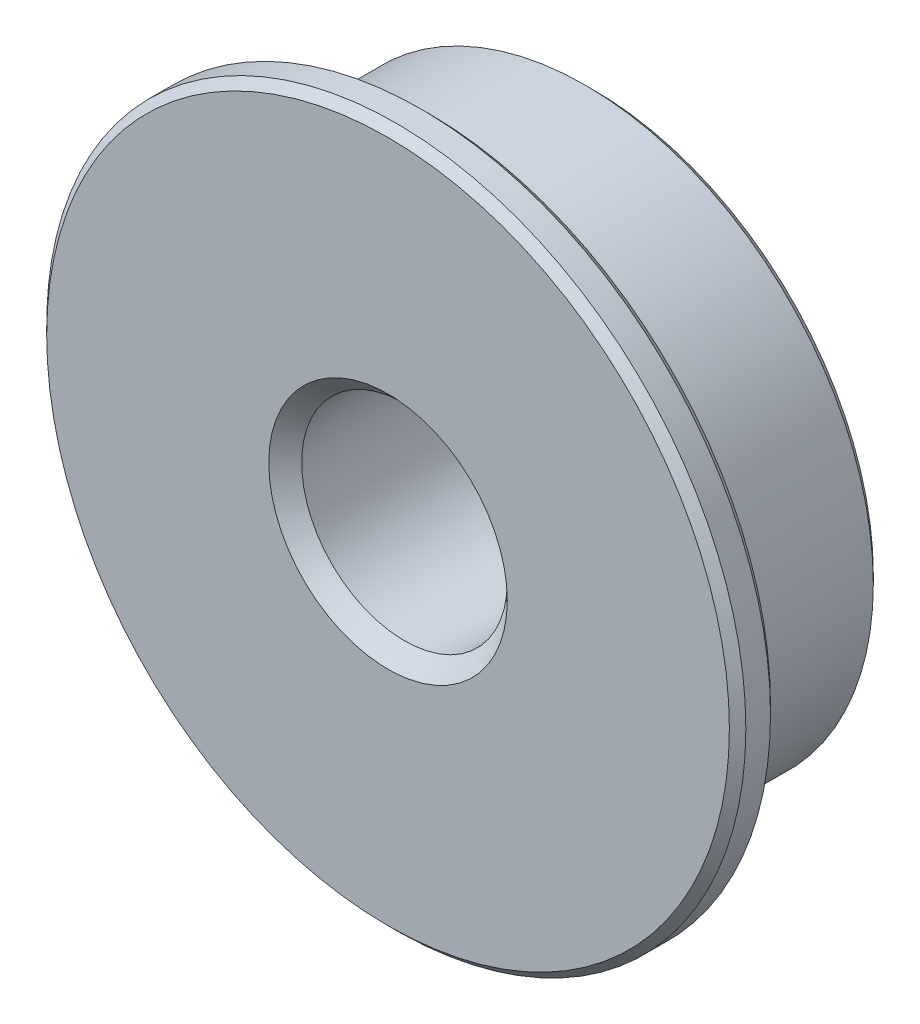
SolidWorks part; units mm, degrees
ref_plane "前视基准面" through (0, 0, 0) normal (0, 0, 1) x (1, 0, 0)
ref_plane "上视基准面" through (0, 0, 0) normal (0, 1, 0) x (1, 0, 0)
ref_plane "右视基准面" through (0, 0, 0) normal (1, 0, 0) x (0, 0, -1)
sketch "草图1" plane through (0, 0, 0) normal (0, 0, 1) x (1, 0, 0)
  circle A0 centre (0, 0) radius 2.5
  circle A1 centre (0, 0) radius 7
  dimension "D1" = 5
  dimension "D2" = 14
extrude "凸台-拉伸1" add sketch "草图1" along normal mid plane 5
sketch "草图2" plane through (0, 0, 2.5) normal (0, 0, 1) x (1, 0, 0)
  circle A0 centre (0, 0) radius 8.5
  circle A1 centre (0, 0) radius 2.5 construction
  circle A2 centre (0, 0) radius 2.5
  dimension "D1" = 17
extrude "凸台-拉伸2" add sketch "草图2" against normal blind 1
chamfer "倒角1" distance 0.2 angle 45 3 edges at (8.5, 0, 1.5) (7, 0, -2.5) (8.5, 0, 2.5)
chamfer "倒角2" distance 0.4 angle 45 2 edges at (2.5, 0, 2.5) (2.5, 0, -2.5)
